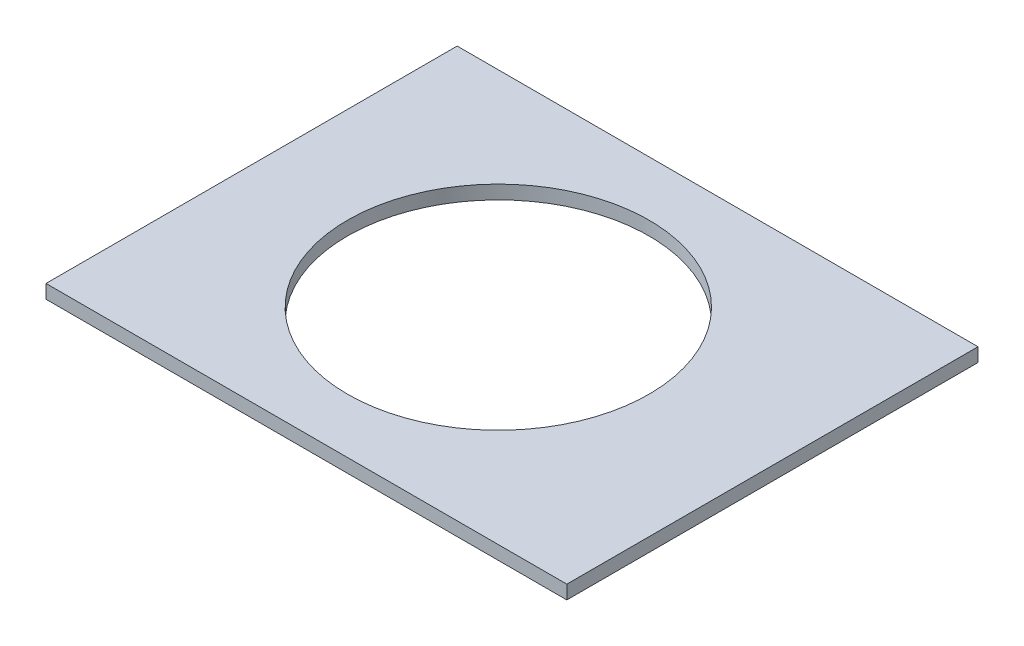
SolidWorks part; units mm, degrees
ref_plane "정면" through (0, 0, 0) normal (0, 0, 1) x (1, 0, 0)
ref_plane "윗면" through (0, 0, 0) normal (0, 1, 0) x (1, 0, 0)
ref_plane "우측면" through (0, 0, 0) normal (1, 0, 0) x (0, 0, -1)
sketch "스케치1" plane through (0, 0, 0) normal (0, 1, 0) x (1, 0, 0)
  line L1 (19, -15) -> (-19, -15)
  line L2 (19, -15) -> (19, 15)
  line L3 (19, 15) -> (-19, 15)
  line L4 (-19, -15) -> (-19, 15)
  line L5 (19, -15) -> (-19, 15) construction
  line L6 (19, 15) -> (-19, -15) construction
  point P0 (0, 0)
  dimension "D1" = 38
  dimension "D2" = 30
extrude "보스-돌출1" add sketch "스케치1" along normal blind 8
sketch "스케치2" plane through (0, 0, 0) normal (0, 1, 0) x (1, 0, 0)
  line L0 (19, 15) -> (-19, 15) construction
  line L1 (-18, 14) -> (19, 14)
  line L2 (-18, 14) -> (-18, -14)
  line L3 (-18, -14) -> (19, -14)
  line L4 (19, 14) -> (19, -14)
  line L5 (-19, 15) -> (-19, -15) construction
  dimension "D1" = 1
  dimension "D2" = 28
  dimension "D3" = 37
  dimension "D4" = 1
extrude "컷-돌출1" cut sketch "스케치2" along normal blind 7 from offset 1
sketch "스케치4" plane through (0, 0, 0) normal (0, 1, 0) x (1, 0, 0)
  line L1 (19, -15) -> (-19, -15)
  line L2 (19, -15) -> (19, 15)
  line L3 (19, 15) -> (-19, 15)
  line L4 (-19, -15) -> (-19, 15)
  line L5 (19, -15) -> (-19, 15) construction
  line L6 (19, 15) -> (-19, -15) construction
  point P0 (0, 0)
extrude "보스-돌출3" add sketch "스케치4" along normal blind 1 from offset 8 separate body
sketch "스케치5" plane through (0, 0, 0) normal (0, 1, 0) x (1, 0, 0)
  line L0 (-19, 15) -> (-19, -15) construction
  line L3 (19, 15) -> (-19, 15) construction
  circle A0 centre (-1, 0) radius 11
  dimension "D1" = 22
  dimension "D2" = 7
  dimension "D3" = 4
extrude "컷-돌출2" cut sketch "스케치5" against normal blind 1 from surface at 9 starting at face at (0, 9, 0)
sketch "스케치7" plane through (0, 0, 0) normal (0, -1, 0) x (1, 0, 0)
  line L4 (-19, 15) -> (-19, -15)
  line L5 (-19, -15) -> (19, -15)
  line L6 (19, -15) -> (19, 15)
  line L7 (19, 15) -> (-19, 15)
  line L8 (-19, 15) -> (-19, -15)
  line L9 (-19, -15) -> (19, -15)
  line L10 (19, -15) -> (19, 15)
  line L11 (19, 15) -> (-19, 15)
  dimension "D1" = 0
extrude "컷-돌출4" cut sketch "스케치7" against normal blind 8
